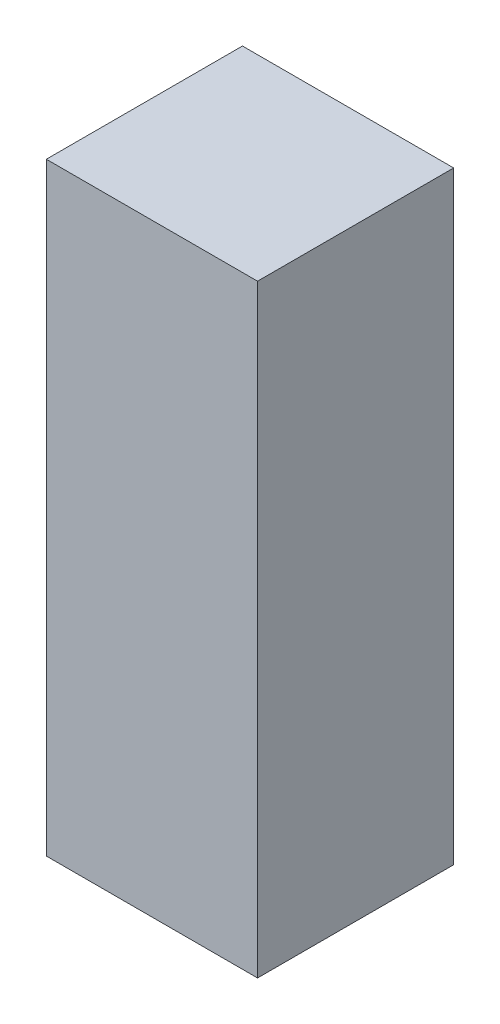
SolidWorks part; units mm, degrees
ref_plane "Front Plane" through (0, 0, 0) normal (0, 0, 1) x (1, 0, 0)
ref_plane "Top Plane" through (0, 0, 0) normal (0, 1, 0) x (1, 0, 0)
ref_plane "Right Plane" through (0, 0, 0) normal (1, 0, 0) x (0, 0, -1)
other "Configuration Table"
sketch "Sketch1" plane through (0, 0, 0) normal (0, 0, 1) x (1, 0, 0)
  line L1 (24, 1040) -> (38, 1040)
  line L2 (24, 1040) -> (24, 1080)
  line L3 (24, 1080) -> (38, 1080)
  line L4 (38, 1040) -> (38, 1080)
extrude "OVEN_yag_kabi_kapagi_mentese_2_1" add sketch "Sketch1" along normal blind 13 from offset 20 separate body
